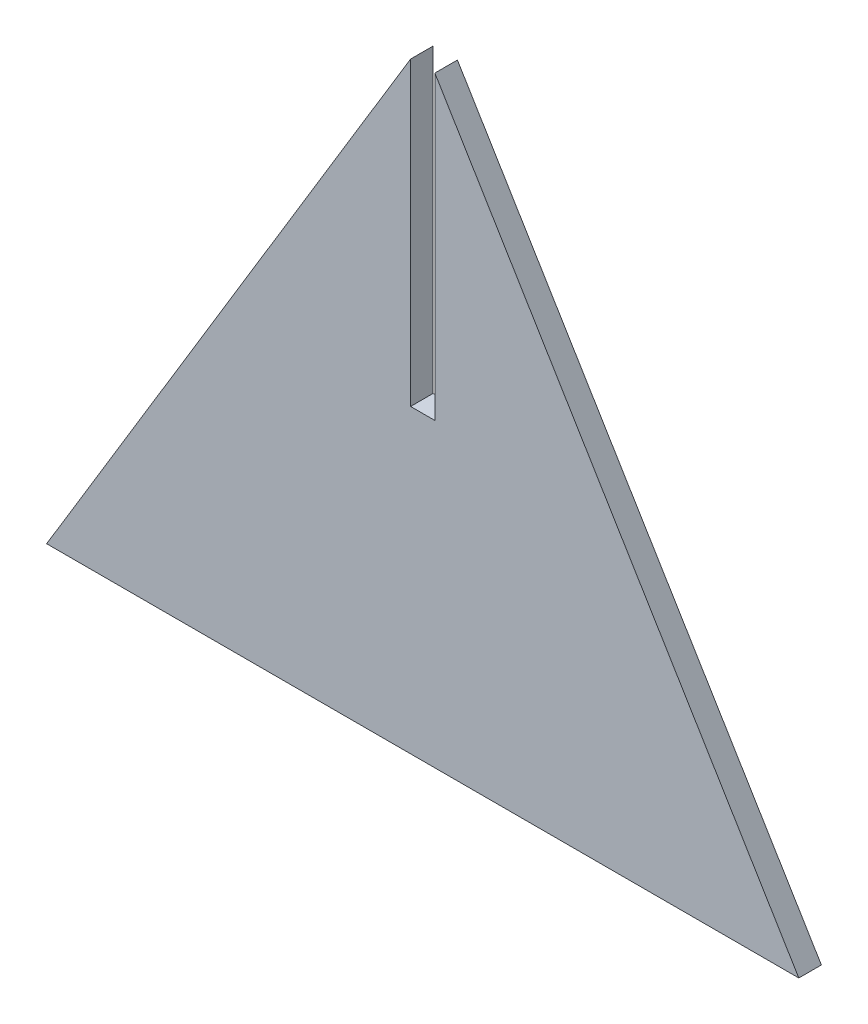
SolidWorks part; units mm, degrees
ref_plane "Alzado" through (0, 0, 0) normal (0, 0, 1) x (1, 0, 0)
ref_plane "Planta" through (0, 0, 0) normal (0, 1, 0) x (1, 0, 0)
ref_plane "Vista lateral" through (0, 0, 0) normal (1, 0, 0) x (0, 0, -1)
sketch "Croquis1" plane through (0, 0, 0) normal (0, 0, 1) x (1, 0, 0)
  line L1 (-5.1029, 80) -> (-53.49, 0)
  line L2 (-1.8771, 40) -> (-1.8771, 80)
  line L4 (-5.1029, 40) -> (-5.1029, 80)
  line L5 (-53.49, 0) -> (-1.8771, 0)
  line L6 (-1.8771, 80) -> (46.51, 0)
  line L7 (46.51, 0) -> (-1.8771, 0)
  line L8 (-5.1029, 40) -> (-1.8771, 40)
  point P0 (0, 0)
  dimension "D1" = 100
  dimension "D2" = 40
  dimension "D3" = 80
  dimension "D4" = 80
extrude "Saliente-Extruir1" add sketch "Croquis1" along normal blind 3
